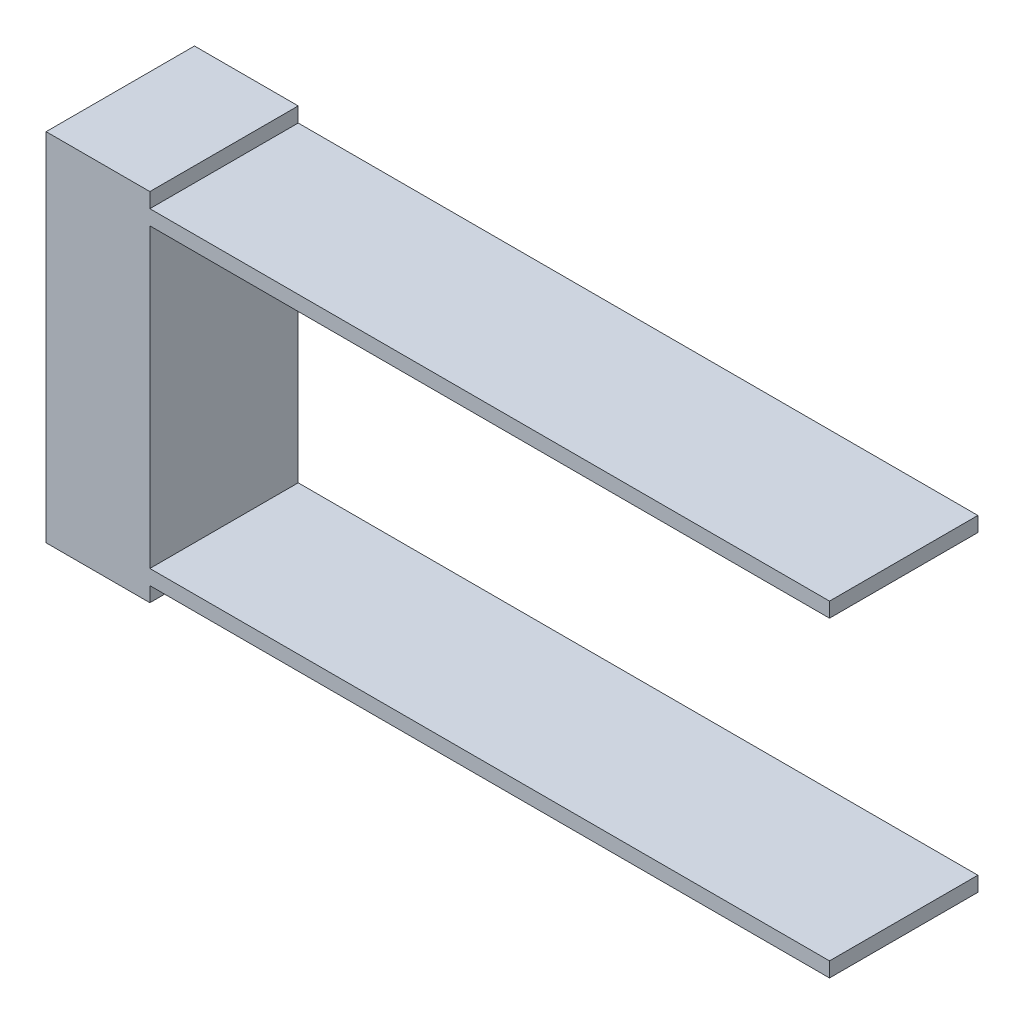
SolidWorks part; units mm, degrees
ref_plane "Front Plane" through (0, 0, 0) normal (0, 0, 1) x (1, 0, 0)
ref_plane "Top Plane" through (0, 0, 0) normal (0, 1, 0) x (1, 0, 0)
ref_plane "Right Plane" through (0, 0, 0) normal (1, 0, 0) x (0, 0, -1)
sketch "Sketch1" plane through (0, 0, 0) normal (0, 0, 1) x (1, 0, 0)
  line L0 (-48.52, 25) -> (-48.52, -25)
  line L1 (66, 27.5) -> (-48.52, 27.5)
  line L2 (66, 27.5) -> (66, 25)
  line L3 (66, 25) -> (-48.52, 25)
  line L5 (-48.52, -25) -> (66, -25)
  line L7 (-48.52, -27.5) -> (66, -27.5)
  line L8 (66, -25) -> (66, -27.5)
  line L9 (-66, 30) -> (-48.52, 30)
  line L10 (-66, 30) -> (-66, -30)
  line L11 (-66, -30) -> (-48.52, -30)
  line L12 (-48.52, 30) -> (-48.52, 27.5)
  line L13 (-48.52, -27.5) -> (-48.52, -30)
  dimension "D1" = 2.5
  dimension "D2" = 2.5
extrude "Boss-Extrude1" add sketch "Sketch1" along normal blind 25 contours L9 L12 L1 L2 L3 L0 L5 L8 L7 L13 L11 L10
